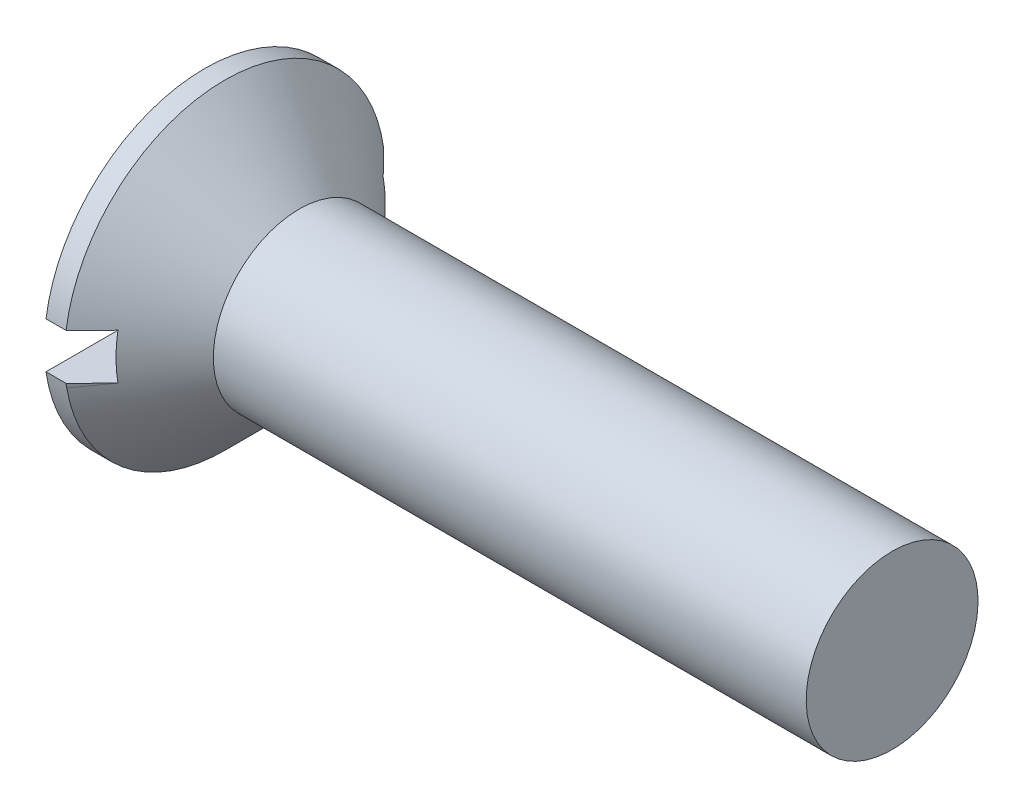
SolidWorks part; units mm, degrees
material "Plain Carbon Steel"
ref_plane "Front Plane" through (0, 0, 0) normal (0, 0, 1) x (1, 0, 0)
ref_plane "Top Plane" through (0, 0, 0) normal (0, 1, 0) x (1, 0, 0)
ref_plane "Right Plane" through (0, 0, 0) normal (1, 0, 0) x (0, 0, -1)
sketch "Sketch1" plane through (0, 0, 0) normal (0, 0, 1) x (1, 0, 0)
  line L0 (0, 0) -> (0, 2.8)
  line L1 (0, 2.8) -> (0.35, 2.8)
  line L2 (0.35, 2.8) -> (1.65, 1.5)
  line L3 (1.65, 1.5) -> (12, 1.5)
  line L4 (12, 1.5) -> (12, 0)
  line L5 (12, 0) -> (0, 0) construction
  line L6 (0, 0) -> (12, 0)
  dimension "D1" = 45
  dimension "D2" = 3
  dimension "D3" = 5.6
  dimension "D4" = 1.65
  dimension "D5" = 12
revolve "Revolve1" add sketch "Sketch1" angle 360 about L5
sketch "Sketch2" plane through (0, 0, 0) normal (-1, 0, 0) x (0, 0, 1)
  line L0 (2.8, 0) -> (-2.8, 0) construction
  line L1 (-2.8, 0.4) -> (2.8, 0.4)
  line L2 (-2.8, 0.4) -> (-2.8, -0.4)
  line L3 (-2.8, -0.4) -> (2.8, -0.4)
  line L4 (2.8, 0.4) -> (2.8, -0.4)
  circle A0 centre (0, 0) radius 2.8 construction
  dimension "D1" = 0.8
extrude "Cut-Extrude1" cut sketch "Sketch2" against normal blind 0.8
